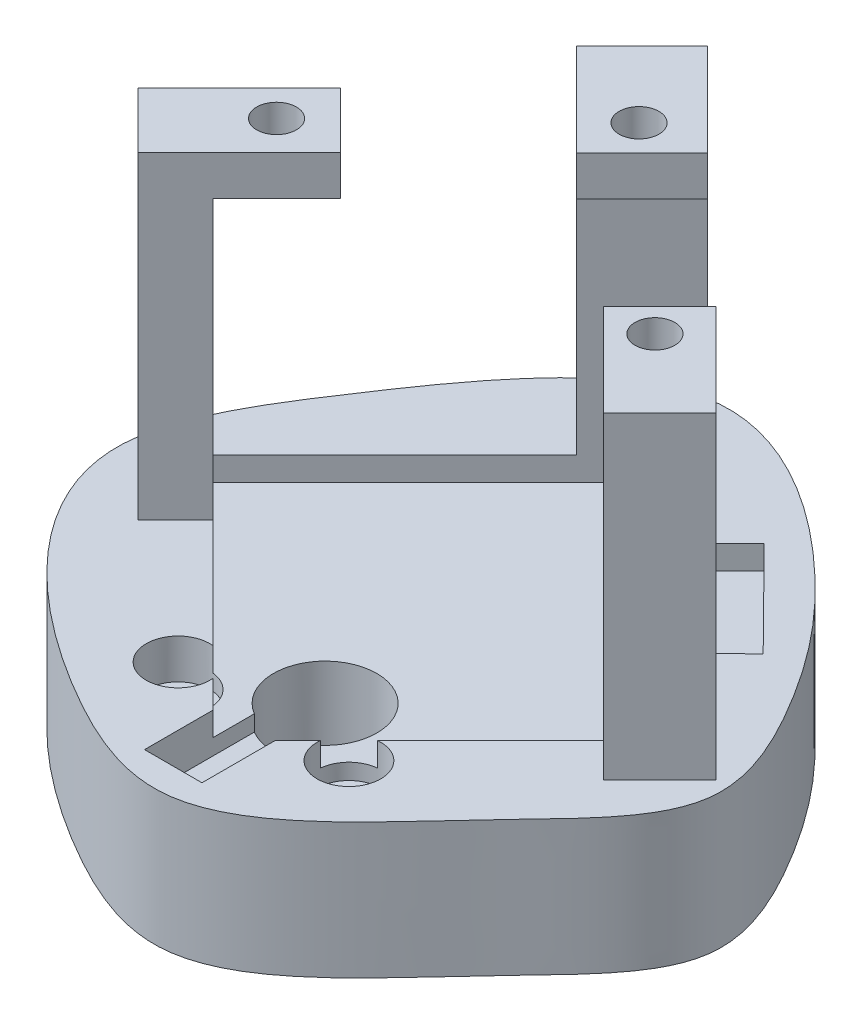
SolidWorks part; units mm, degrees
ref_plane "Front Plane" through (0, 0, 0) normal (0, 0, 1) x (1, 0, 0)
ref_plane "Top Plane" through (0, 0, 0) normal (0, 1, 0) x (1, 0, 0)
ref_plane "Right Plane" through (0, 0, 0) normal (1, 0, 0) x (0, 0, -1)
sketch "Sketch2" plane through (0, 0, 0) normal (0, 1, 0) x (1, 0, 0)
  circle A0 centre (0, 0) radius 60
extrude "Boss-Extrude1" add sketch "Sketch2" along normal blind 17 contours A0
sketch "Sketch4" plane through (0, 17, 0) normal (0, 1, 0) x (1, 0, 0)
  circle A0 centre (0, 0) radius 6.5
  dimension "D1" = 13
extrude "Cut-Extrude1" cut sketch "Sketch4" against normal blind 17 contours A0
sketch "Sketch6" plane through (0, 17, 0) normal (0, 1, 0) x (1, 0, 0)
  line L0 (-5.9779, 23.0428) -> (5.9779, 10.9572)
  line L1 (-5.9779, 23.0428) -> (13.2168, 42.0313)
  line L2 (5.9779, 10.9572) -> (25.1725, 29.9458)
  line L3 (13.2168, 42.0313) -> (25.1725, 29.9458)
  point P2 (15.5752, 20.4515)
  point P5 (3.6195, 32.537)
  dimension "D1" = 17
  dimension "D2" = 27
sketch "Sketch7" plane through (0, 17, 0) normal (0, 1, 0) x (1, 0, 0)
  circle A0 centre (-10.75, -7.75) radius 4
  dimension "D1" = 8
extrude "Cut-Extrude2" cut sketch "Sketch7" against normal blind 5 contours A0
mirror "Mirror1" about plane through (0, 0, 0) normal (1, 0, 0) of "Cut-Extrude2"
sketch "Sketch8" plane through (0, 17, 0) normal (0, 1, 0) x (1, 0, 0)
  line L1 (-3.3067, -5.596) -> (3.9199, -5.596)
  line L2 (-3.3067, -5.596) -> (-3.3067, -19.4129)
  line L3 (-3.3067, -19.4129) -> (3.9199, -19.4129)
  line L4 (3.9199, -5.596) -> (3.9199, -19.4129)
  circle A0 centre (0, 0) radius 6.5 construction
extrude "Cut-Extrude3" cut sketch "Sketch8" against normal blind 5
sketch "Sketch9" plane through (0, 17, 0) normal (0, 1, 0) x (1, 0, 0)
  line L0 (-31.1127, 17) -> (0, 48.1127)
  line L1 (-31.1127, 17) -> (0, -14.1127)
  line L2 (0, 48.1127) -> (31.1127, 17)
  line L3 (0, -14.1127) -> (31.1127, 17)
  dimension "D1" = 44
  dimension "D2" = 44
extrude "Cut-Extrude4" cut sketch "Sketch9" against normal blind 3
extrude "Cut-Extrude5" cut sketch "Sketch6" against normal blind 3
sketch "Sketch11" plane through (0, 17, 0) normal (0, 1, 0) x (1, 0, 0)
  line L0 (0, 48.1127) -> (-8.24, 39.8727)
  line L1 (0, 48.1127) -> (-4.5593, 52.672)
  line L2 (-8.24, 39.8727) -> (-12.7993, 44.432)
  line L3 (-4.5593, 52.672) -> (-12.7993, 44.432)
  line L4 (-31.1127, 17) -> (-24.0416, 9.9289)
  line L5 (-31.1127, 17) -> (-35.8263, 12.2864)
  line L6 (-24.0416, 9.9289) -> (-28.7552, 5.2154)
  line L7 (-35.8263, 12.2864) -> (-28.7552, 5.2154)
  line L8 (-31.1127, 17) -> (-10.3418, -3.7709) construction
  line L9 (31.6446, 17.5319) -> (24.5735, 10.4608)
  line L10 (31.6446, 17.5319) -> (35.9355, 13.241)
  line L11 (24.5735, 10.4608) -> (28.8645, 6.1699)
  line L12 (35.9355, 13.241) -> (28.8645, 6.1699)
  line L13 (10.3418, -3.7709) -> (31.1127, 17) construction
  line L14 (0, 48.1127) -> (-31.1127, 17) construction
  dimension "D1" = 11.6531
  dimension "D2" = 10
  dimension "D3" = 10
extrude "Boss-Extrude2" add sketch "Sketch11" along normal blind 35
sketch "Sketch12" plane through (0, 52, 0) normal (0, 1, 0) x (1, 0, 0)
  line L0 (-4.5593, 52.672) -> (-12.7993, 44.432)
  line L1 (-4.5593, 52.672) -> (7.108, 41.0047)
  line L2 (-12.7993, 44.432) -> (-1.132, 32.7647)
  line L3 (7.108, 41.0047) -> (-1.132, 32.7647)
  line L4 (-35.8263, 12.2864) -> (-28.7552, 5.2154)
  line L5 (-35.8263, 12.2864) -> (-23.0984, 25.0143)
  line L6 (-28.7552, 5.2154) -> (-16.0273, 17.9433)
  line L7 (-23.0984, 25.0143) -> (-16.0273, 17.9433)
  line L8 (35.9355, 13.241) -> (28.8645, 6.1699)
  line L9 (35.9355, 13.241) -> (24.3378, 24.8387)
  line L10 (28.8645, 6.1699) -> (17.2667, 17.7677)
  line L11 (24.3378, 24.8387) -> (17.2667, 17.7677)
extrude "Boss-Extrude3" add sketch "Sketch12" along normal blind 5
sketch "Sketch13" plane through (0, 57, 0) normal (0, 1, 0) x (1, 0, 0)
  circle A0 centre (-0.5, 40) radius 2.5
  dimension "D1" = 5
sketch "Sketch14" plane through (0, 57, 0) normal (0, 1, 0) x (1, 0, 0)
  circle A0 centre (23.5, 18) radius 2.5
sketch "Sketch15" plane through (0, 57, 0) normal (0, 1, 0) x (1, 0, 0)
  circle A0 centre (-23.777, 17.669) radius 2.5
extrude "Cut-Extrude7" cut sketch "Sketch13" against normal blind 5 contours A0
extrude "Cut-Extrude8" cut sketch "Sketch15" against normal blind 5 contours A0
extrude "Cut-Extrude9" cut sketch "Sketch14" against normal blind 5 contours A0
sketch "Sketch16" plane through (0, 17, 0) normal (0, 1, 0) x (1, 0, 0)
  spline S0 degree 3 poles (-27.5345, 35.3123) (-7.4919, 63.2621) (20.1768, 43.1639) (32.0959, 27.7397) (41.1035, 9.3847) (23.4414, -7.0123) (7.3872, -27.6695) (-20.6756, -15.2656) (-45.2159, 6.8631) (-27.5345, 35.3123) (-7.4919, 63.2621) (20.1768, 43.1639) knots -0.41993 -0.246246 -0.147029 0 0.129983 0.21607 0.283536 0.368924 0.507401 0.58007 0.753754 0.852971 1 1.129983 1.21607 1.283536 only from (-4.7945, 54.4115) to (-4.7945, 54.4115)
extrude "Cut-Extrude10" cut sketch "Sketch16" against normal blind 17
